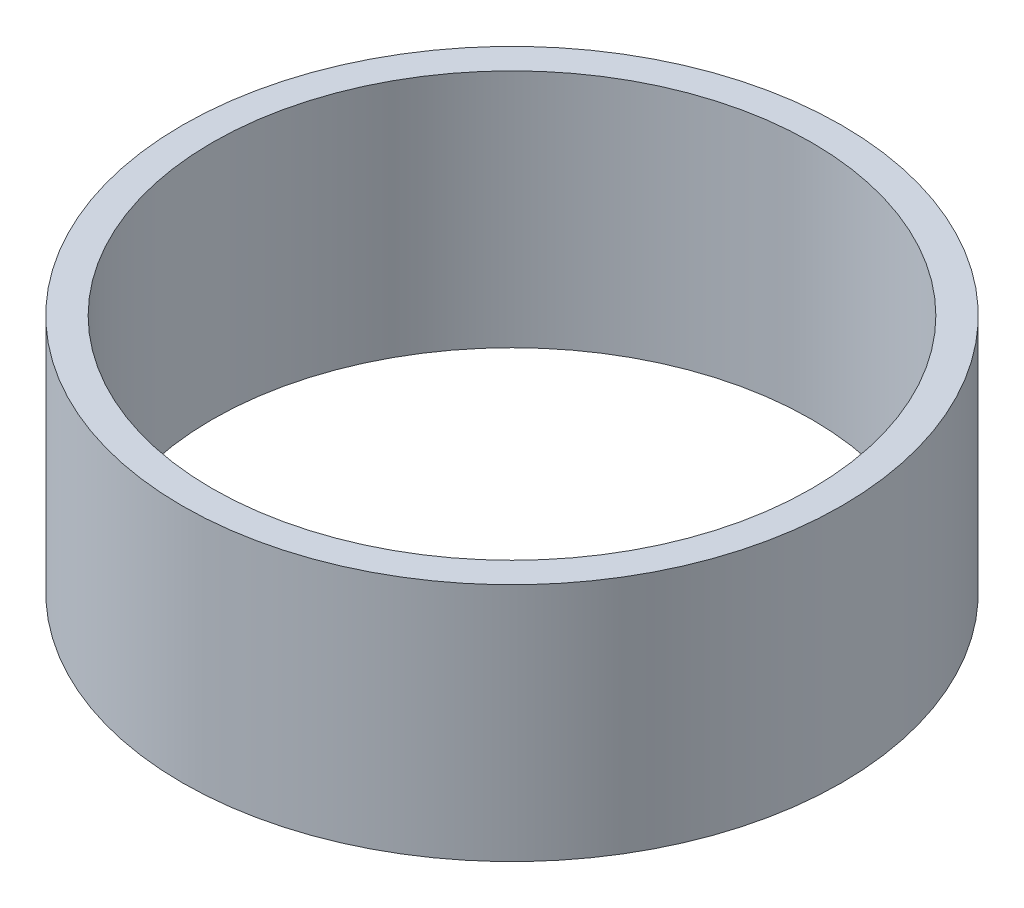
SolidWorks part; units mm, degrees
ref_plane "Front Plane" through (0, 0, 0) normal (0, 0, 1) x (1, 0, 0)
ref_plane "Top Plane" through (0, 0, 0) normal (0, 1, 0) x (1, 0, 0)
ref_plane "Right Plane" through (0, 0, 0) normal (1, 0, 0) x (0, 0, -1)
sketch "Sketch1" plane through (0, 0, 0) normal (0, 1, 0) x (1, 0, 0)
  circle A0 centre (0, 0) radius 11
  dimension "D1" = 22
extrude "Boss-Extrude1" add sketch "Sketch1" along normal blind 8
sketch "Sketch2" plane through (0, 8, 0) normal (0, 1, 0) x (1, 0, 0)
  circle A0 centre (0, 0) radius 10
  dimension "D1" = 20
extrude "Cut-Extrude1" cut sketch "Sketch2" against normal through all
